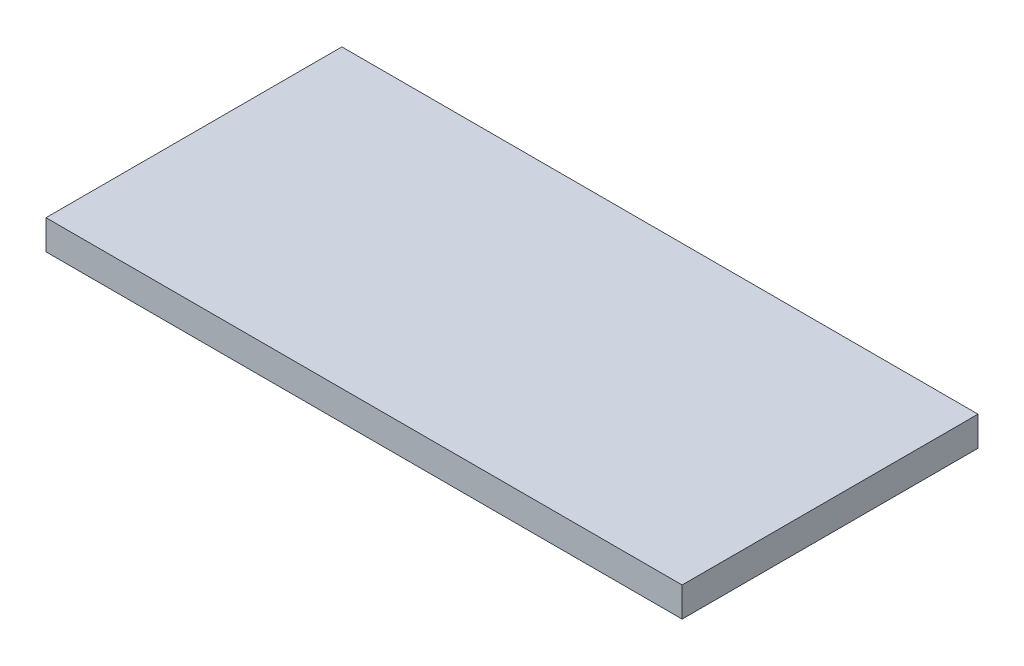
SolidWorks part; units mm, degrees
ref_plane "Front Plane" through (0, 0, 0) normal (0, 0, 1) x (1, 0, 0)
ref_plane "Top Plane" through (0, 0, 0) normal (0, 1, 0) x (1, 0, 0)
ref_plane "Right Plane" through (0, 0, 0) normal (1, 0, 0) x (0, 0, -1)
sketch "Sketch1" plane through (0, 0, 0) normal (0, 1, 0) x (1, 0, 0)
  line L1 (0, 0) -> (43, 0)
  line L2 (0, 0) -> (0, 20)
  line L3 (0, 20) -> (43, 20)
  line L4 (43, 0) -> (43, 20)
  dimension "D1" = 20
  dimension "D2" = 43
extrude "Boss-Extrude1" add sketch "Sketch1" along normal blind 2
